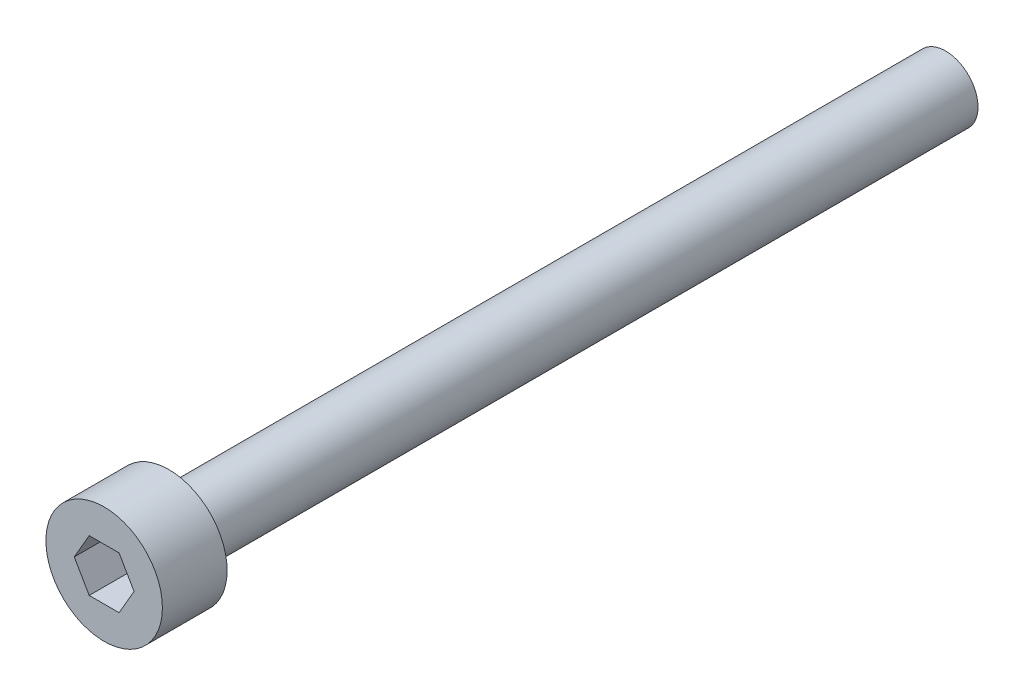
SolidWorks part; units mm, degrees
ref_plane "Plan de face" through (0, 0, 0) normal (0, 0, 1) x (1, 0, 0)
ref_plane "Plan de dessus" through (0, 0, 0) normal (0, 1, 0) x (1, 0, 0)
ref_plane "Plan de droite" through (0, 0, 0) normal (1, 0, 0) x (0, 0, -1)
sketch "Esquisse1" plane through (0, 0, 0) normal (0, 0, 1) x (1, 0, 0)
  circle A0 centre (0, 0) radius 1.25
  dimension "D1" = 2.5
extrude "Boss.-Extru.1" add sketch "Esquisse1" along normal blind 30
sketch "Esquisse2" plane through (0, 0, 30) normal (0, 0, 1) x (1, 0, 0)
  circle A0 centre (0, 0) radius 2.25
  dimension "D1" = 4.5
extrude "Boss.-Extru.2" add sketch "Esquisse2" along normal blind 2.5
sketch "Esquisse3" plane through (0, 0, 32.5) normal (0, 0, 1) x (1, 0, 0)
  line L1 (1.1547, 0) -> (0.5774, 1)
  line L2 (0.5774, 1) -> (-0.5774, 1)
  line L3 (-0.5774, 1) -> (-1.1547, 0)
  line L4 (-1.1547, 0) -> (-0.5774, -1)
  line L5 (-0.5774, -1) -> (0.5774, -1)
  line L6 (0.5774, -1) -> (1.1547, 0)
  circle A0 centre (0, 0) radius 1 construction
  dimension "D1" = 2
extrude "Enlèv. mat.-Extru.1" cut sketch "Esquisse3" against normal blind 1.5
